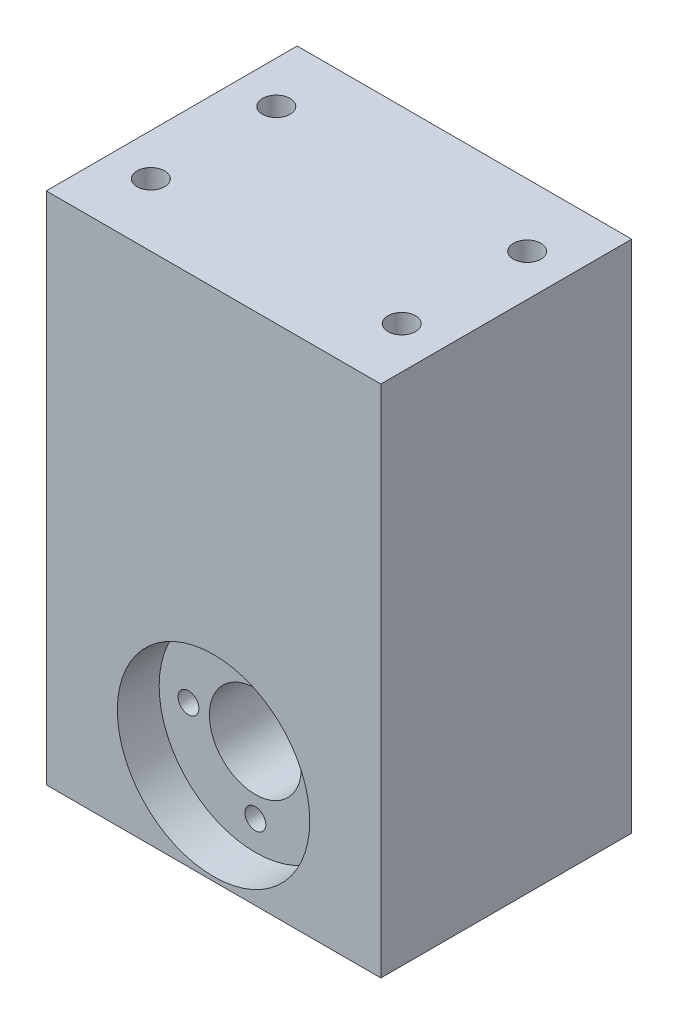
SolidWorks part; units mm, degrees
material "3.3535 (EN-AW 5754)"
ref_plane "Ön Düzlem" through (0, 0, 0) normal (0, 0, 1) x (1, 0, 0)
ref_plane "Üst Düzlem" through (0, 0, 0) normal (0, 1, 0) x (1, 0, 0)
ref_plane "Sağ Düzlem" through (0, 0, 0) normal (1, 0, 0) x (0, 0, -1)
sketch "Sketch1" plane through (0, 0, 0) normal (0, 0, 1) x (1, 0, 0)
  line L0 (-20, 62.5) -> (-20, 0)
  line L3 (-20, 0) -> (20, 0)
  line L7 (20, 62.5) -> (-20, 62.5)
  line L8 (0, -41.6296) -> (0, 41.6296) construction
  line L9 (20, 62.5) -> (20, 0)
  point P1 (-20, 0)
  point P5 (20, 0)
  point P12 (0, 0)
  dimension "D1" = 62.5
  dimension "D4" = 40
extrude "Boss-Extrude1" add sketch "Sketch1" along normal mid plane 30
sketch "Sketch2" plane through (0, 0, 15) normal (0, 0, 1) x (1, 0, 0)
  circle A0 centre (0, 13) radius 11.5
  dimension "D1" = 23
  dimension "D2" = 13
extrude "Cut-Extrude1" cut sketch "Sketch2" against normal blind 5
sketch "Sketch3" plane through (0, 0, 10) normal (0, 0, 1) x (1, 0, 0)
  circle A0 centre (0, 13) radius 5.5
  dimension "D1" = 11
extrude "Cut-Extrude2" cut sketch "Sketch3" against normal through all
hole_wizard "M4 Tapped Hole1" positions "Sketch4" profile "Sketch5" tap size "M4" standard "ISO"
sketch "Sketch4" plane through (0, 62.5, 0) normal (0, 1, 0) x (1, 0, 0)
  line L0 (0, 0) -> (-20, 0) construction
  line L1 (-20, -15) -> (-20, 15) construction
  line L3 (0, 0) -> (0, 15) construction
  line L4 (20, 15) -> (-20, 15) construction
  point P0 (-15, 7.5)
  point P2 (15, 7.5)
  point P4 (15, -7.5)
  point P6 (-15, -7.5)
  dimension "D1" = 30
  dimension "D2" = 15
cosmetic thread "Hole Thread5" parameters "D1"=8, "D2"=4
cosmetic thread "Hole Thread6" parameters "D1"=8, "D2"=4
cosmetic thread "Hole Thread7" parameters "D1"=8, "D2"=4
cosmetic thread "Hole Thread8" parameters "D1"=8, "D2"=4
sketch "Sketch5" plane through (-15, 62.5, -7.5) normal (1, 0, 0) x (0, 0, 1)
  line L0 (0, 0) -> (0, 12.4914)
  line L1 (0, 12.4914) -> (1.65, 11.5)
  line L2 (1.65, 11.5) -> (1.65, 0)
  line L5 (1.65, 0) -> (0, 0)
  line L10 (0, 12.4914) -> (-1.65, 11.5) construction
  line L11 (0, -6.35) -> (0, 107.95) construction
  dimension "Tap Drill Dia." = 3.3
  dimension "Tap Drill Depth" = 11.5
  dimension "Drill Angle" = 118
sketch "Sketch6" plane through (0, 0, 10) normal (0, 0, 1) x (1, 0, 0)
  circle A0 centre (0, 13) radius 8 construction
  circle A1 centre (0, 21) radius 1.25
  circle A2 centre (9, 13) radius 1.25
  circle A3 centre (1, 4) radius 1.25
  circle A4 centre (-8, 12) radius 1.25
  point P14 (0.5, 12.5)
  dimension "D1" = 16
  dimension "D2" = 2.5
  dimension "D3" = 4
extrude "Cut-Extrude3" [suppressed] cut sketch "Sketch6" against normal through all
hole_wizard "M3 Tapped Hole2" positions "Sketch7" profile "Sketch8" tap size "M3" standard "ISO" end condition through all
sketch "Sketch7" plane through (0, 0, 10) normal (0, 0, 1) x (1, 0, 0)
  line L1 (0, 5) -> (0, 21) construction
  line L5 (8, 13) -> (-8, 13) construction
  circle A0 centre (0, 13) radius 8 construction
  point P11 (0, 21)
  point P76 (0, 5)
  point P77 (0, 13)
  point P87 (-8, 13)
  point P137 (8, 13)
  point P138 (0, 13)
  dimension "D2" = 16
  dimension "D1" = 13
sketch "Sketch8" plane through (0, 13, 10) normal (1, 0, 0) x (0, -1, 0)
  line L0 (0, 0) -> (0, 25)
  line L1 (0, 25) -> (1.25, 25)
  line L2 (1.25, 25) -> (1.25, 0)
  line L5 (1.25, 0) -> (0, 0)
  line L11 (0, -6.35) -> (0, 107.95) construction
  dimension "Thru Tap Drill Dia." = 2.5
  dimension "Thru Tap Drill Depth" = 25
cosmetic thread "Hole Thread1" parameters "D2"=3
cosmetic thread "Hole Thread2" parameters "D2"=3
cosmetic thread "Hole Thread3" parameters "D2"=3
cosmetic thread "Hole Thread4" parameters "D2"=3
sketch "Sketch9" plane through (0, 0, 15) normal (0, 0, 1) x (1, 0, 0)
  line L0 (20, 0) -> (20, 62.5) construction
  line L1 (-20, 0) -> (20, 0)
  line L2 (-20, 0) -> (-20, 1)
  line L3 (-20, 1) -> (20, 1)
  line L4 (20, 0) -> (20, 1)
  dimension "D1" = 1
extrude "Cut-Extrude4" cut sketch "Sketch9" against normal through all
